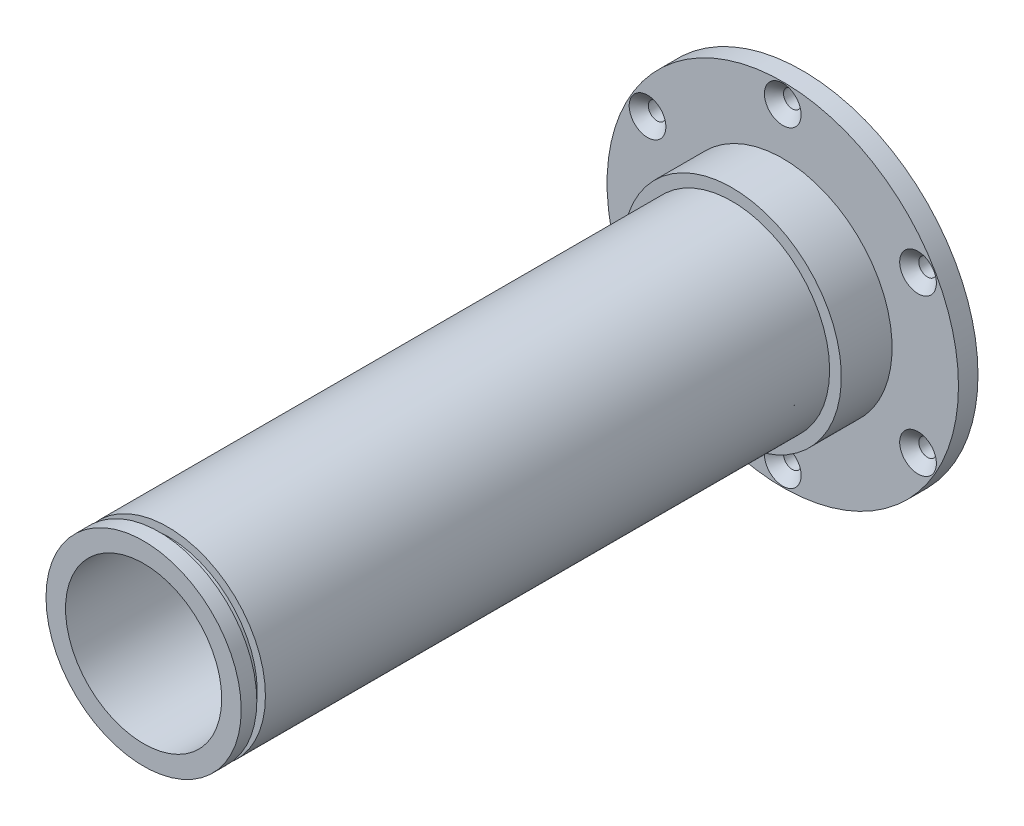
SolidWorks part; units mm, degrees
material "7079 Alloy"
ref_plane "Front Plane" through (0, 0, 0) normal (0, 0, 1) x (1, 0, 0)
ref_plane "Top Plane" through (0, 0, 0) normal (0, 1, 0) x (1, 0, 0)
ref_plane "Right Plane" through (0, 0, 0) normal (1, 0, 0) x (0, 0, -1)
sketch "Sketch1" plane through (0, 0, 0) normal (0, 0, 1) x (1, 0, 0)
  line L0 (0, 0) -> (0, 40) construction
  line L2 (0, 0) -> (0, -40) construction
  circle A0 centre (0, 0) radius 45
  circle A1 centre (-34.641, -20) radius 2
  circle A2 centre (0, 0) radius 40 construction
  circle A3 centre (-34.641, 20) radius 2
  circle A4 centre (0, 40) radius 2
  circle A5 centre (0, -40) radius 2
  circle A6 centre (34.641, 20) radius 2
  circle A7 centre (34.641, -20) radius 2
  dimension "D1" = 4
  dimension "D3" = 90
  dimension "D2" = 40
extrude "Extrude1" add sketch "Sketch1" along normal blind 5
sketch "Sketch2" plane through (0, 0, 5) normal (0, 0, 1) x (1, 0, 0)
  circle A0 centre (0, 0) radius 28
  dimension "D1" = 56
extrude "Extrude2" add sketch "Sketch2" along normal blind 13
sketch "Sketch3" plane through (0, 0, 18) normal (0, 0, 1) x (1, 0, 0)
  circle A0 centre (0, 0) radius 25
  dimension "D1" = 50
extrude "Extrude3" add sketch "Sketch3" along normal blind 150.7
sketch "Sketch4" plane through (0, 0, 168.7) normal (0, 0, 1) x (1, 0, 0)
  circle A0 centre (0, 0) radius 20
  dimension "D1" = 40
extrude "Cut-Extrude1" cut sketch "Sketch4" against normal blind 200
sketch "Sketch5" plane through (0, 0, 168.7) normal (0, 0, 1) x (1, 0, 0)
  circle A0 centre (0, 0) radius 22.9
  circle A1 centre (0, 0) radius 25 construction
  circle A2 centre (0, 0) radius 25
  dimension "D1" = 45.8
extrude "Cut-Extrude2" cut sketch "Sketch5" against normal blind 2.2 from offset 4 offset against normal yes
sketch "Sketch6" plane through (0, 0, 0) normal (0, 0, -1) x (-1, 0, 0)
  circle A0 centre (0, 0) radius 20 construction
  circle A1 centre (0, 0) radius 25
  circle A2 centre (0, 0) radius 20
  dimension "D1" = 50
extrude "Boss-Extrude1" add sketch "Sketch6" along normal blind 3
hole_wizard "CSK for M4 Flat Head Machine Screw1" positions "Sketch8" profile "Sketch7" countersink size "M4" standard "Ansi Metric" end condition through all
sketch "Sketch8" plane through (0, 0, 5) normal (0, 0, 1) x (1, 0, 0)
  point P1 (34.641, -20)
  point P4 (0, -40)
  point P7 (-34.641, -20)
  point P10 (-34.641, 20)
  point P13 (0, 40)
  point P16 (34.641, 20)
sketch "Sketch7" plane through (34.641, -20, 5) normal (1, 0, 0) x (0, -1, 0)
  line L0 (0, 0) -> (0, 8)
  line L1 (0, 8) -> (2.25, 8)
  line L2 (2.25, 8) -> (2.25, 2.45)
  line L3 (2.25, 2.45) -> (4.7, 0)
  line L5 (4.7, 0) -> (0, 0)
  line L6 (-2.25, 2.45) -> (-4.7, 0) construction
  line L11 (0, -6.35) -> (0, 107.95) construction
  dimension "Thru Hole Dia." = 4.5
  dimension "Thru Hole Depth" = 8
  dimension "Near C'Sink Dia." = 9.4
  dimension "Near C'Sink Angle" = 90
